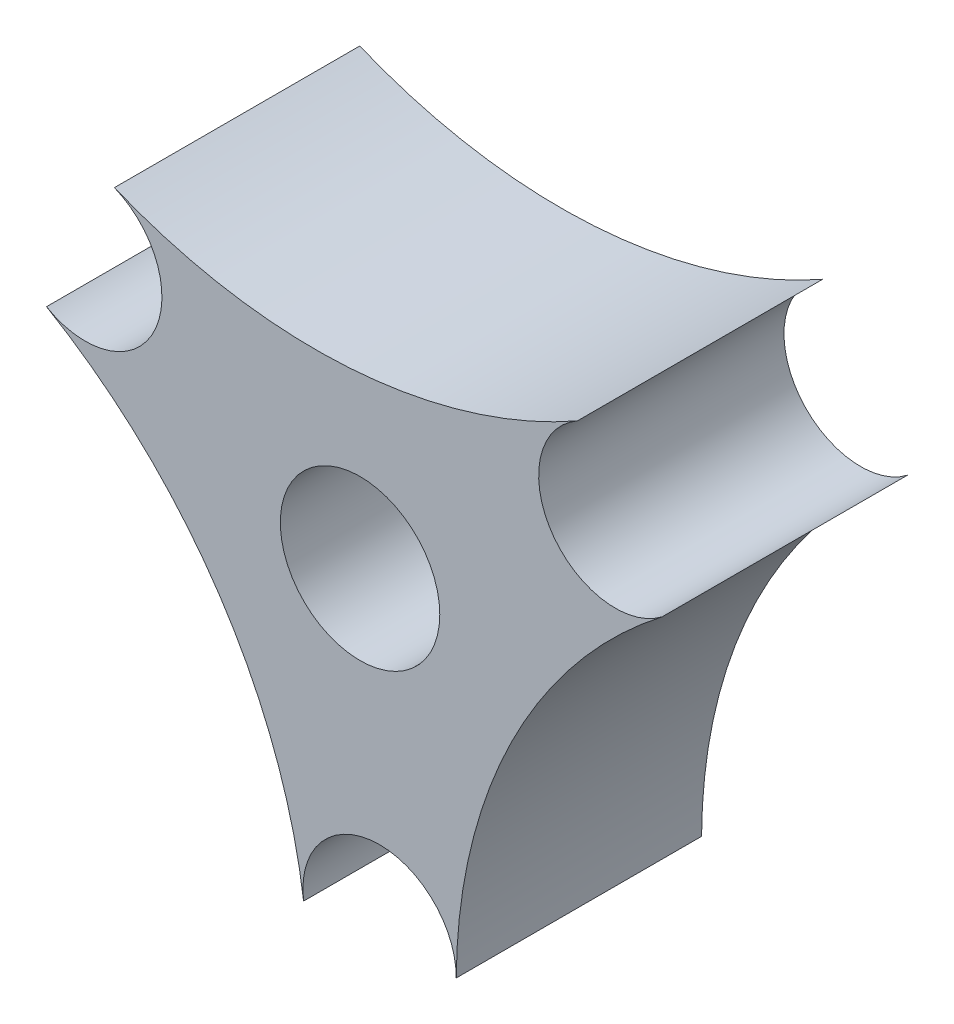
SolidWorks part; units mm, degrees
ref_plane "Front Plane" through (0, 0, 0) normal (0, 0, 1) x (1, 0, 0)
ref_plane "Top Plane" through (0, 0, 0) normal (0, 1, 0) x (1, 0, 0)
ref_plane "Right Plane" through (0, 0, 0) normal (1, 0, 0) x (0, 0, -1)
sketch "Sketch1" plane through (0, 0, 0) normal (0, 0, 1) x (1, 0, 0)
  circle A2 centre (0, 0) radius 200 construction
  circle A7 centre (166.4871, 110.8244) radius 50
  circle A8 centre (166.4871, 110.8244) radius 12.5
  circle A9 centre (12.7332, -199.5943) radius 50
  circle A10 centre (12.7332, -199.5943) radius 12.5
  circle A11 centre (-179.2203, 88.7699) radius 50
  circle A12 centre (-179.2203, 88.7699) radius 12.5
  arc A15 (-160.2306, 135.0235) -> (141.7738, 154.2899) centre (-29.0048, 454.6543) ccw
  arc A16 (-36.8184, -206.2756) -> (-204.5059, 45.6348) centre (-379.2398, -252.446) ccw
  arc A18 (197.0491, 71.2521) -> (62.7321, -199.9247) centre (408.2445, -202.2083) ccw
  circle A19 centre (0, 0) radius 52
  point P22 (0, 0)
  dimension "D1" = 400
  dimension "D3" = 100
  dimension "D2" = 25
  dimension "D4" = 3
  dimension "D5" = 691.04
  dimension "D6" = 691.04
  dimension "D7" = 691.04
  dimension "D8" = 104
  dimension "D9" = 179.2203
extrude "Boss-Extrude1" add sketch "Sketch1" along normal blind 160 contours A18 A7 A15 A11 A16 A9 A19
